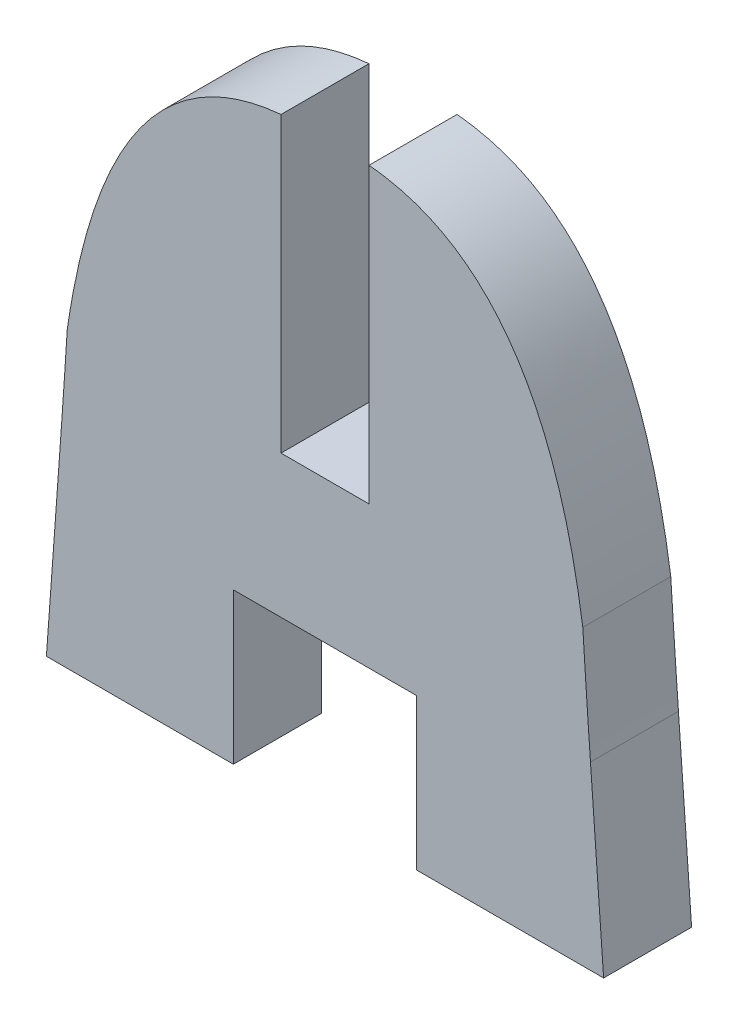
SolidWorks part; units mm, degrees
material "Pinho"
ref_plane "Plano frontal" through (0, 0, 0) normal (0, 0, 1) x (1, 0, 0)
ref_plane "Plano superior" through (0, 0, 0) normal (0, 1, 0) x (1, 0, 0)
ref_plane "Plano direito" through (0, 0, 0) normal (1, 0, 0) x (0, 0, -1)
sketch "Esboço1" plane through (0, 0, 0) normal (0, 0, 1) x (1, 0, 0)
  line L0 (19, 0) -> (12.625, 0)
  line L1 (8, 10) -> (8, 20)
  line L2 (19, 0) -> (18.5514, 6.1516)
  line L3 (0, 0) -> (0.4486, 6.1516)
  line L4 (8, 10) -> (11, 10)
  line L5 (6.375, 0) -> (0, 0)
  line L6 (11, 20) -> (11, 10)
  line L8 (12.625, 5.15) -> (12.625, 0)
  line L9 (12.625, 5.15) -> (11, 5.15)
  line L10 (6.375, 5.15) -> (6.375, 0)
  line L11 (8, 5.15) -> (6.375, 5.15)
  line L14 (8, 5.15) -> (11, 5.15)
  arc A0 (18.5514, 6.1516) -> (18.29, 10) centre (407.5188, 34.5138) cw
  arc A1 (0.4486, 6.1516) -> (0.71, 10) centre (-388.5188, 34.5138) ccw
  spline S0 degree 2 poles (18.29, 10) (16.9127, 19.4595) (11, 20) knots 0 0 0 0.891893 0.891893 0.891893
  spline S1 degree 2 poles (0.71, 10) (2.0873, 19.4595) (8, 20) knots 0 0 0 0.891893 0.891893 0.891893
extrude "Ressalto-extrusão1" add sketch "Esboço1" along normal blind 3
